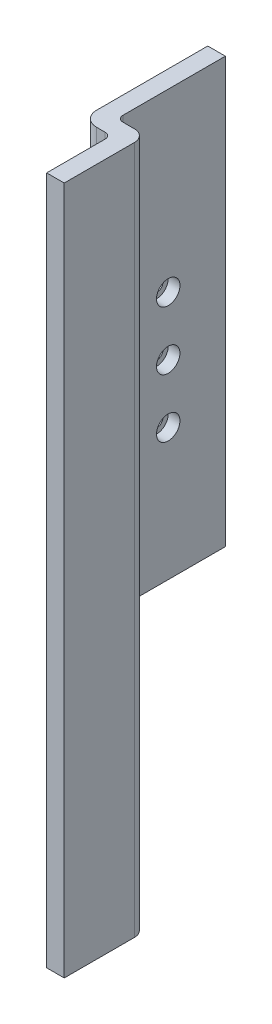
SolidWorks part; units mm, degrees
ref_plane "Piano frontale" through (0, 0, 0) normal (0, 0, 1) x (1, 0, 0)
ref_plane "Piano superiore" through (0, 0, 0) normal (0, 1, 0) x (1, 0, 0)
ref_plane "Piano destro" through (0, 0, 0) normal (1, 0, 0) x (0, 0, -1)
ref_plane "Piano1" through (0, 0, 0) normal (-1, 0, 0) x (0, -1, 0)
sketch "Schizzo1" plane through (0, 0, 0) normal (-1, 0, 0) x (0, -1, 0)
  line L0 (0, -43) -> (0, 22)
  line L1 (0, 22) -> (-235, 22)
  line L2 (-235, 22) -> (-235, -43)
  line L3 (-235, -43) -> (0, -43)
  dimension "D1" = 235
  dimension "D2" = 65
extrude "Estrusione-Estrusione1" add sketch "Schizzo1" against normal blind 16
sketch "Schizzo2" plane through (0, 0, 0) normal (0, -1, 0) x (1, 0, 0)
  line L0 (16, -43) -> (16, -6)
  line L1 (16, -6) -> (6, -6)
  line L2 (6, -6) -> (6, -43)
  line L3 (6, -43) -> (16, -43)
  line L4 (0, -43) -> (0, 22) construction
  dimension "D1" = 6
  dimension "D2" = 16
  dimension "D3" = 37
extrude "Taglio-Estrusione1" cut sketch "Schizzo2" against normal through all
sketch "Schizzo3" plane through (0, 0, 0) normal (-1, 0, 0) x (0, 0, 1)
  line L0 (-8, 0) -> (-8, 90)
  line L1 (-8, 90) -> (-43, 90)
  line L2 (-43, 90) -> (-43, 0)
  line L3 (-43, 0) -> (-8, 0)
  line L4 (-43, 0) -> (22, 0) construction
  line L5 (-43, 235) -> (-43, 0) construction
  dimension "D1" = 35
  dimension "D2" = 90
extrude "Taglio-Estrusione2" cut sketch "Schizzo3" against normal through all
sketch "Schizzo4" plane through (0, 0, 0) normal (0, -1, 0) x (1, 0, 0)
  line L0 (0, 0) -> (10, 0)
  line L1 (10, 0) -> (10, 22)
  line L2 (10, 22) -> (0, 22)
  line L3 (0, 22) -> (0, 0)
  line L4 (6, -6) -> (6, -8) construction
  line L5 (16, -6) -> (6, -6) construction
  dimension "D1" = 4
  dimension "D2" = 6
  dimension "D3" = 6
  dimension "D4" = 28
extrude "Taglio-Estrusione3" cut sketch "Schizzo4" against normal through all
hole_wizard "Foro lamato per Vite M4 a testa esagonale-1" positions "Schizzo6" profile "Schizzo5" counterbore size "M4" standard "Ansi Metric"
sketch "Schizzo6" plane through (6, 0, 0) normal (1, 0, 0) x (0, 0, -1)
  point P0 (23.5, 175)
  point P1 (23.5, 155)
  point P2 (23.5, 135)
sketch "Schizzo5" plane through (6, 175, -23.5) normal (0, 1, 0) x (0, 0, -1)
  line L0 (0, 0) -> (0, 6)
  line L1 (0, 6) -> (2.25, 6)
  line L3 (2.25, 6) -> (2.25, 4)
  line L4 (2.25, 4) -> (4, 4)
  line L5 (4, 4) -> (4, 0)
  line L7 (4, 0) -> (0, 0)
  line L11 (0, -6.35) -> (0, 107.95) construction
  dimension "Thru Hole Dia." = 4.5
  dimension "Thru Hole Depth" = 6
  dimension "C'Bore Dia." = 8
  dimension "C'Bore Depth" = 4
fillet "Raccordo1" radius 2 2 edges at (10, 117.5, 0) (6, 117.5, -6)
fillet "Raccordo2" radius 4 1 edges at (16, 117.5, -6)
fillet "Raccordo3" radius 5 1 edges at (0, 117.5, 0)
fillet "Raccordo4" radius 6 1 edges at (3, 90, -8)
